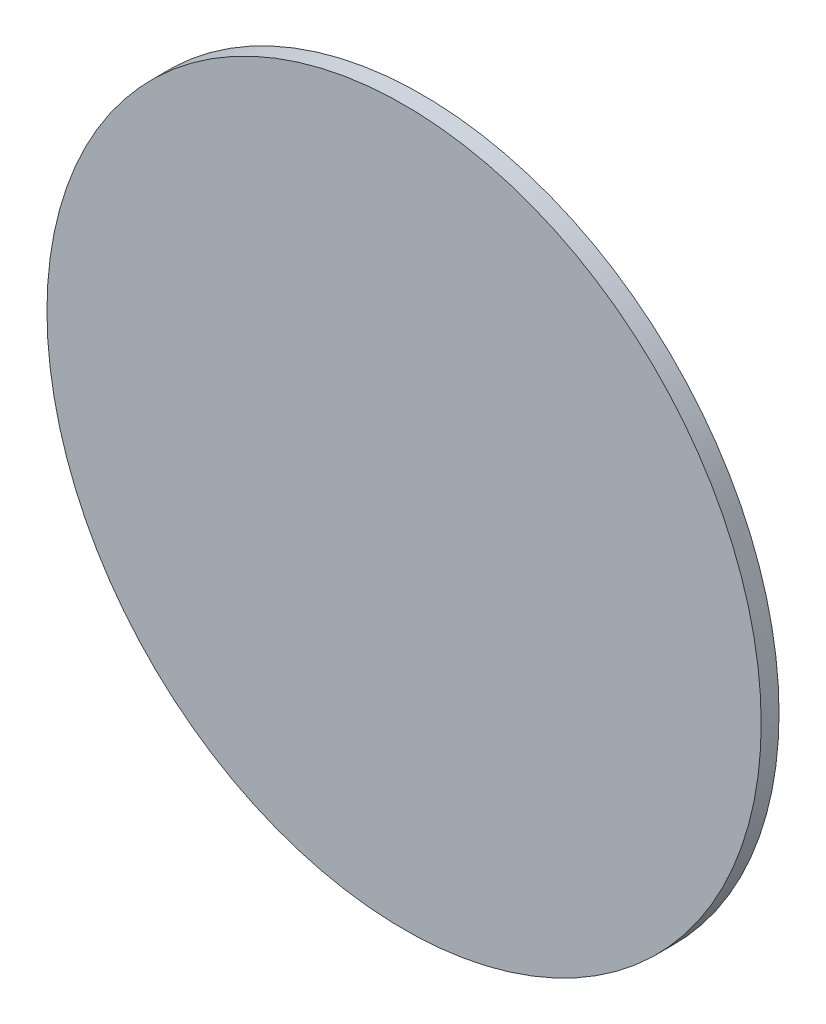
SolidWorks part; units mm, degrees
ref_plane "Front Plane" through (0, 0, 0) normal (0, 0, 1) x (1, 0, 0)
ref_plane "Top Plane" through (0, 0, 0) normal (0, 1, 0) x (1, 0, 0)
ref_plane "Right Plane" through (0, 0, 0) normal (1, 0, 0) x (0, 0, -1)
sketch "Sketch1" plane through (0, 0, 0) normal (0, 0, 1) x (1, 0, 0)
  circle A0 centre (0, 0) radius 20
  dimension "D1" = 40
extrude "Boss-Extrude1" add sketch "Sketch1" along normal blind 1
